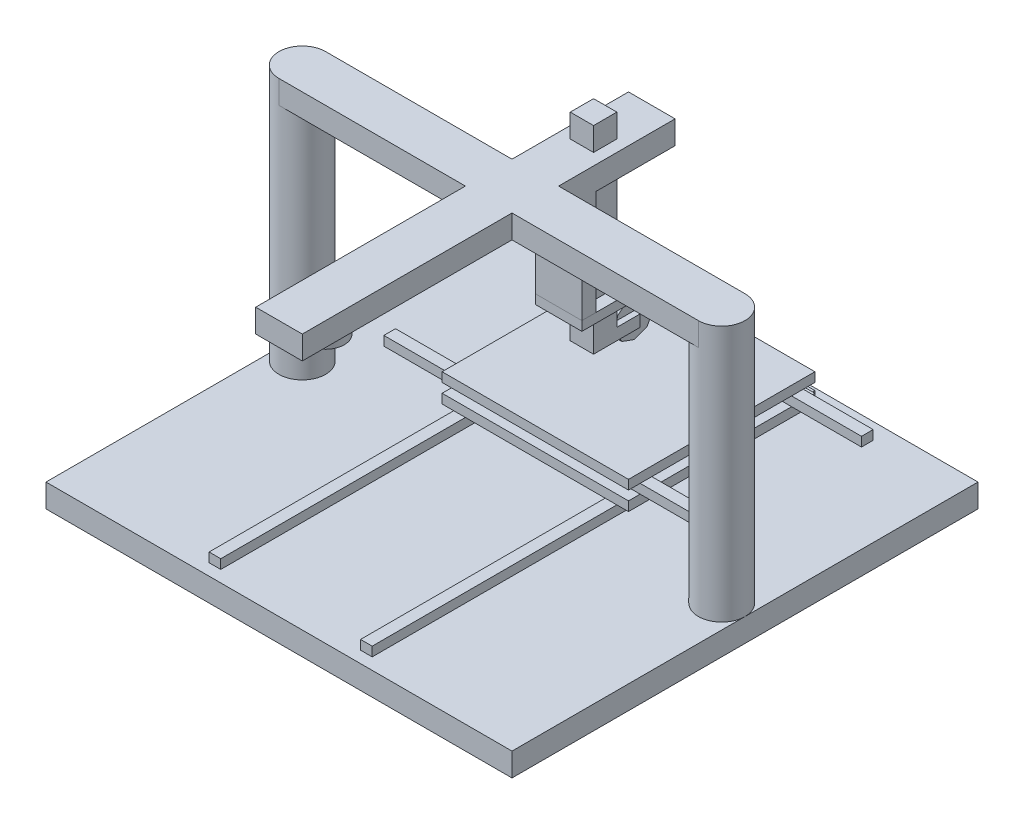
SolidWorks part; units mm, degrees
ref_plane "Front Plane" through (0, 0, 0) normal (0, 0, 1) x (1, 0, 0)
ref_plane "Top Plane" through (0, 0, 0) normal (0, 1, 0) x (1, 0, 0)
ref_plane "Right Plane" through (0, 0, 0) normal (1, 0, 0) x (0, 0, -1)
sketch "Sketch3" plane through (0, 0, 0) normal (0, 1, 0) x (1, 0, 0)
  line L1 (0, 0) -> (100, 0)
  line L2 (0, 0) -> (0, 100)
  line L3 (0, 100) -> (100, 100)
  line L4 (100, 0) -> (100, 100)
  circle A0 centre (0, 50) radius 5
  circle A1 centre (100, 50) radius 5
extrude "Boss-Extrude1" add sketch "Sketch3" along normal blind 5 contours L2 L3 L4 L1
sketch "Sketch6" plane through (0, 0, 0) normal (0, -1, 0) x (-1, 0, 0)
  circle A0 centre (-5, 50) radius 5
extrude "Boss-Extrude3" add sketch "Sketch6" against normal blind 55
sketch "Sketch9" plane through (0, 0, 0) normal (0, -1, 0) x (-1, 0, 0)
  circle A0 centre (-95, 50) radius 5
extrude "Boss-Extrude4" add sketch "Sketch9" against normal blind 55
sketch "Sketch19" plane through (0, 55, 0) normal (0, 1, 0) x (1, 0, 0)
  circle A0 centre (5, 50) radius 5
  circle A1 centre (95, 50) radius 5
sketch "Sketch20" plane through (0, 55, 0) normal (0, 1, 0) x (1, 0, 0)
  line L1 (5, 45) -> (95, 45)
  line L2 (5, 45) -> (5, 55)
  line L3 (5, 55) -> (95, 55)
  line L4 (95, 45) -> (95, 55)
  circle A0 centre (5, 50) radius 5 construction
  circle A1 centre (95, 50) radius 5 construction
extrude "Boss-Extrude6" add sketch "Sketch20" along normal blind 5
sketch "Sketch21" plane through (0, 55, 0) normal (0, 1, 0) x (1, 0, 0)
  circle A0 centre (5, 50) radius 5
extrude "Boss-Extrude7" add sketch "Sketch21" along normal blind 5
sketch "Sketch22" plane through (0, 55, 0) normal (0, 1, 0) x (1, 0, 0)
  line L0 (95, 45) -> (95, 55) construction
  circle A0 centre (95, 50) radius 5
extrude "Boss-Extrude8" add sketch "Sketch22" along normal blind 5
sketch "Sketch24" plane through (0, 55, 0) normal (0, -1, 0) x (-1, 0, 0)
  line L0 (-45, 0) -> (-55, 0)
  line L1 (-45, 0) -> (-45, 80)
  line L2 (-55, 0) -> (-55, 80)
  line L3 (-45, 80) -> (-55, 80)
extrude "Boss-Extrude9" add sketch "Sketch24" against normal blind 5
sketch "Sketch27" plane through (0, 55, 0) normal (0, -1, 0) x (-1, 0, 0)
  circle A0 centre (-50, 10) radius 4
extrude "Boss-Extrude11" add sketch "Sketch27" along normal blind 2.5
sketch3d "3DSketch5"
  line L1 (30, 7, -55) -> (30, 7, -95)
  line L2 (30, 7, -55) -> (70, 7, -55)
  line L3 (70, 7, -55) -> (70, 7, -95)
  line L4 (30, 7, -95) -> (70, 7, -95)
  line L5 (30, 7, -55) -> (70, 7, -95) construction
  line L6 (70, 7, -55) -> (30, 7, -95) construction
  point P0 (50, 7, -75)
extrude "Boss-Extrude16" add sketch "3DSketch5" along direction (0, 1, 0) on the side of the normal blind 2 separate body
sketch "Sketch31" plane through (0, 5, 0) normal (0, 1, 0) x (1, 0, 0)
  line L1 (32.5, 97.5) -> (35, 97.5)
  line L2 (32.5, 97.5) -> (32.5, 2.5)
  line L3 (32.5, 2.5) -> (35, 2.5)
  line L4 (35, 97.5) -> (35, 2.5)
extrude "Boss-Extrude17" add sketch "Sketch31" along normal blind 2
sketch "Sketch32" plane through (0, 5, 0) normal (0, 1, 0) x (1, 0, 0)
  line L1 (65, 97.5) -> (67.5, 97.5)
  line L2 (65, 97.5) -> (65, 2.5)
  line L3 (65, 2.5) -> (67.5, 2.5)
  line L4 (67.5, 97.5) -> (67.5, 2.5)
extrude "Boss-Extrude18" add sketch "Sketch32" along normal blind 2
sketch3d "3DSketch6"
  line L1 (15, 9, -90) -> (15, 9, -92.5)
  line L2 (15, 9, -90) -> (85, 9, -90)
  line L3 (85, 9, -90) -> (85, 9, -92.5)
  line L4 (15, 9, -92.5) -> (85, 9, -92.5)
extrude "Boss-Extrude19" add sketch "3DSketch6" along direction (0, 1, 0) on the side of the normal blind 2
sketch3d "3DSketch7"
  line L1 (15, 9, -60) -> (15, 9, -57.5)
  line L2 (15, 9, -60) -> (85, 9, -60)
  line L3 (85, 9, -60) -> (85, 9, -57.5)
  line L4 (15, 9, -57.5) -> (85, 9, -57.5)
extrude "Boss-Extrude20" add sketch "3DSketch7" along direction (0, 1, 0) on the side of the normal blind 2
sketch3d "3DSketch10"
  line L1 (30, 11, -95) -> (30, 11, -55)
  line L2 (30, 11, -95) -> (70, 11, -95)
  line L3 (70, 11, -95) -> (70, 11, -55)
  line L4 (30, 11, -55) -> (70, 11, -55)
extrude "Boss-Extrude21" add sketch "3DSketch10" along direction (0, 1, 0) on the side against the normal blind 2
sketch3d "3DSketch15"
  line L1 (52.5, 65, -65) -> (52.5, 65, -70)
  line L2 (52.5, 65, -65) -> (47.5, 65, -65)
  line L3 (47.5, 65, -65) -> (47.5, 65, -70)
  line L4 (52.5, 65, -70) -> (47.5, 65, -70)
extrude "Boss-Extrude23" add sketch "3DSketch15" along direction (0, 1, 0) on the side of the normal blind 42.5
sketch "Sketch33" plane through (0, 60, 0) normal (0, 1, 0) x (1, 0, 0)
  line L1 (47.5, 65) -> (52.5, 65)
  line L2 (47.5, 65) -> (47.5, 70)
  line L3 (47.5, 70) -> (52.5, 70)
  line L4 (52.5, 65) -> (52.5, 70)
extrude "Cut-Extrude2" cut sketch "Sketch33" against normal blind 5
sketch3d "3DSketch16"
  line L0 (45, 55, -55) -> (45, 55, -80) construction
  line L1 (45, 55, -60) -> (55, 55, -60)
  line L2 (45, 55, -60) -> (45, 32.5, -60)
  line L3 (45, 32.5, -60) -> (55, 32.5, -60)
  line L4 (55, 55, -60) -> (55, 32.5, -60)
extrude "Boss-Extrude24" add sketch "3DSketch16" along direction (0, 0, 1) on the side against the normal blind 3
sketch3d "3DSketch17"
  line L1 (52.5, 22.5, -70) -> (52.5, 25, -70)
  line L2 (52.5, 22.5, -70) -> (52.5, 22.5, -75)
  line L3 (52.5, 22.5, -75) -> (52.5, 25, -75)
  line L4 (52.5, 25, -70) -> (52.5, 25, -75)
extrude "Boss-Extrude25" add sketch "3DSketch17" along direction (1, 0, 0) on the side against the normal blind 1.25
sketch3d "3DSketch18"
  line L1 (47.5, 22.5, -70) -> (47.5, 25, -70)
  line L2 (47.5, 22.5, -70) -> (47.5, 22.5, -75)
  line L3 (47.5, 22.5, -75) -> (47.5, 25, -75)
  line L4 (47.5, 25, -70) -> (47.5, 25, -75)
extrude "Boss-Extrude26" add sketch "3DSketch18" along direction (-1, 0, 0) on the side of the normal blind 1.25 separate body
sketch "Sketch36" plane through (48.75, 0, 0) normal (1, 0, 0) x (0, 0, -1)
  line L0 (75, 22.5) -> (75, 25) construction
  line L1 (76.4196, 27.6504) -> (73.5804, 27.6504)
  line L2 (73.5804, 27.6504) -> (71.4054, 25.8254)
  line L3 (71.4054, 25.8254) -> (70.9123, 23.0292)
  line L4 (70.9123, 23.0292) -> (72.332, 20.5703)
  line L5 (72.332, 20.5703) -> (75, 19.5993)
  line L6 (75, 19.5993) -> (77.668, 20.5703)
  line L7 (77.668, 20.5703) -> (79.0877, 23.0292)
  line L8 (79.0877, 23.0292) -> (78.5946, 25.8254)
  line L9 (78.5946, 25.8254) -> (76.4196, 27.6504)
  circle A0 centre (75, 23.75) radius 3.9004 construction
extrude "Boss-Extrude28" add sketch "Sketch36" along normal blind 2.5
sketch "Sketch37" plane through (48.75, 0, 0) normal (-1, 0, 0) x (0, 0, 1)
  line L0 (-75, 22.5) -> (-75, 25) construction
  circle A0 centre (-75, 23.75) radius 0.5
extrude "Cut-Extrude3" cut sketch "Sketch37" against normal blind 2.5
sketch3d "3DSketch28"
  line L1 (55, 32.5, -60) -> (55, 32.5, -80)
  line L2 (55, 32.5, -60) -> (45, 32.5, -60)
  line L3 (45, 32.5, -60) -> (45, 32.5, -80)
  line L4 (55, 32.5, -80) -> (45, 32.5, -80)
extrude "Boss-Extrude31" add sketch "3DSketch28" along direction (0, -1, 0) on the side of the normal blind 2 separate body
sketch "Sketch38" plane through (0, 32.5, 0) normal (0, 1, 0) x (1, 0, 0)
  line L1 (52, 73) -> (48, 73)
  line L2 (52, 73) -> (52, 77)
  line L3 (52, 77) -> (48, 77)
  line L4 (48, 73) -> (48, 77)
extrude "Cut-Extrude4" cut sketch "Sketch38" against normal blind 2
sketch3d "3DSketch30"
  line L0 (52, 32.5, -73) -> (52, 34, -73)
  line L2 (52, 34, -73) -> (52, 34, -77)
  line L3 (52, 34, -73) -> (48, 34, -73)
  line L4 (48, 34, -73) -> (48, 34, -77)
  line L5 (52, 34, -77) -> (48, 34, -77)
extrude "Boss-Extrude32" add sketch "3DSketch30" along direction (0, 1, 0) on the side of the normal blind 4.5 separate body contours L4 L5 L2 L3
